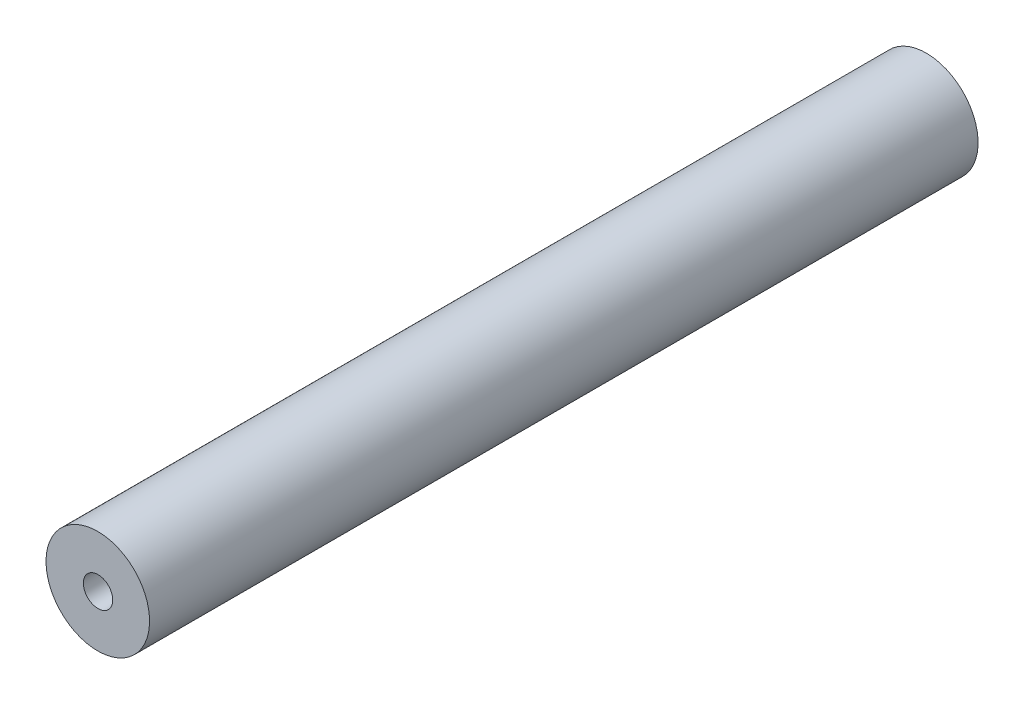
SolidWorks part; units mm, degrees
ref_plane "Front Plane" through (0, 0, 0) normal (0, 0, 1) x (1, 0, 0)
ref_plane "Top Plane" through (0, 0, 0) normal (0, 1, 0) x (1, 0, 0)
ref_plane "Right Plane" through (0, 0, 0) normal (1, 0, 0) x (0, 0, -1)
sketch "Sketch2" plane through (0, 0, 0) normal (0, 0, 1) x (1, 0, 0)
  circle A0 centre (0, 0) radius 4.7625
  dimension "D1" = 9.525
extrude "Boss-Extrude1" add sketch "Sketch2" along normal blind 76.2
hole_wizard "#10-32 Tapped Hole1" positions "Sketch4" profile "Sketch3" tap size "#10-32" standard "Ansi Inch"
sketch "Sketch4" plane through (0, 0, 0) normal (0, 0, -1) x (-1, 0, 0)
  point P0 (-0.0287, 0.0674)
sketch "Sketch3" plane through (0.0287, 0.0674, 0) normal (1, 0, 0) x (0, 1, 0)
  line L0 (0, 0) -> (0, 16.4533)
  line L1 (0, 16.4533) -> (2.0193, 15.24)
  line L2 (2.0193, 15.24) -> (2.0193, 0)
  line L5 (2.0193, 0) -> (0, 0)
  line L10 (0, 16.4533) -> (-2.0193, 15.24) construction
  line L11 (0, -6.35) -> (0, 107.95) construction
  dimension "Tap Drill Dia." = 4.0386
  dimension "Tap Drill Depth" = 15.24
  dimension "Drill Angle" = 118
cosmetic thread "Hole Thread1" parameters "D1"=9.652, "D2"=4.826
ref_point "Point1"
hole_wizard "#6-32 Tapped Hole1" positions "Sketch8" profile "Sketch7" tap size "#6-32" standard "Ansi Inch"
sketch "Sketch8" plane through (0, 0, 76.2) normal (0, 0, 1) x (1, 0, 0)
  point P0 (0.0237, -0.0156)
sketch "Sketch7" plane through (0.0237, -0.0156, 76.2) normal (1, 0, 0) x (0, -1, 0)
  line L0 (0, 0) -> (0, 10.2107)
  line L1 (0, 10.2107) -> (1.3525, 9.398)
  line L2 (1.3525, 9.398) -> (1.3525, 0)
  line L5 (1.3525, 0) -> (0, 0)
  line L10 (0, 10.2107) -> (-1.3526, 9.398) construction
  line L11 (0, -6.35) -> (0, 107.95) construction
  dimension "Tap Drill Dia." = 2.7051
  dimension "Tap Drill Depth" = 9.398
  dimension "Drill Angle" = 118
cosmetic thread "Hole Thread2" parameters "D1"=7.112, "D2"=3.5052
